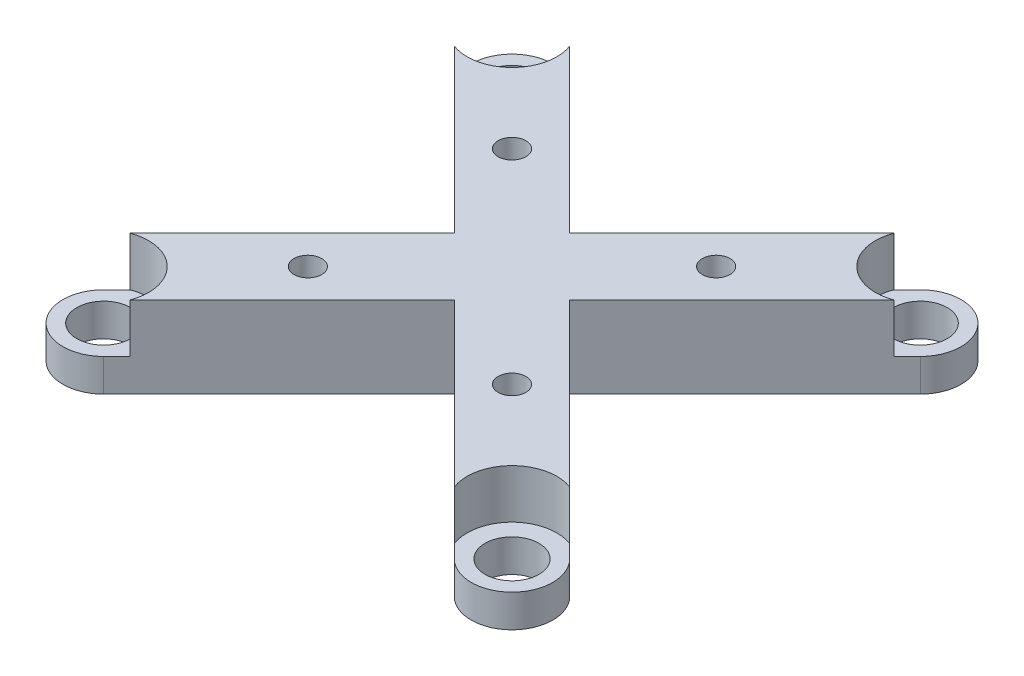
SolidWorks part; units mm, degrees
ref_plane "Front Plane" through (0, 0, 0) normal (0, 0, 1) x (1, 0, 0)
ref_plane "Top Plane" through (0, 0, 0) normal (0, 1, 0) x (1, 0, 0)
ref_plane "Right Plane" through (0, 0, 0) normal (1, 0, 0) x (0, 0, -1)
sketch "Sketch1" plane through (0, 0, 0) normal (0, 1, 0) x (1, 0, 0)
  line L0 (7.0711, 0) -> (28.5355, 21.4645)
  line L1 (0, 40.829) -> (0, -52.7147) construction
  line L2 (-50.9666, 0) -> (60.5221, 0) construction
  line L3 (0, 7.0711) -> (21.4645, 28.5355)
  line L4 (-7.0711, 0) -> (-28.5355, -21.4645)
  line L5 (0, 7.0711) -> (-21.4645, 28.5355)
  line L6 (-7.0711, 0) -> (-28.5355, 21.4645)
  line L7 (0, -7.0711) -> (-21.4645, -28.5355)
  line L8 (0, -7.0711) -> (21.4645, -28.5355)
  line L9 (7.0711, 0) -> (28.5355, -21.4645)
  arc A0 (-28.5355, 21.4645) -> (-21.4645, 28.5355) centre (-25, 25) cw
  arc A1 (28.5355, 21.4645) -> (21.4645, 28.5355) centre (25, 25) ccw
  arc A2 (28.5355, -21.4645) -> (21.4645, -28.5355) centre (25, -25) cw
  arc A3 (-28.5355, -21.4645) -> (-21.4645, -28.5355) centre (-25, -25) ccw
extrude "Extrude1" add sketch "Sketch1" along normal blind 10
hole_wizard "CBORE for M6 SHCS2" positions "3DSketch3" profile "Sketch4" counterbore size "M6" standard "Ansi Metric" end condition through all
sketch3d "3DSketch3"
  line L0 (-25, 10, -25) -> (-25, 0, -25) construction
  point P0 (-25, 10, -25)
sketch "Sketch4" plane through (-25, 10, -25) normal (1, 0, 0) x (0, 0, 1)
  line L0 (0, 0) -> (0, 10)
  line L1 (0, 10) -> (3.3, 10)
  line L3 (3.3, 10) -> (3.3, 6)
  line L4 (3.3, 6) -> (5.5, 6)
  line L5 (5.5, 6) -> (5.5, 0)
  line L7 (5.5, 0) -> (0, 0)
  line L11 (0, -6.35) -> (0, 107.95) construction
  dimension "Thru Hole Dia." = 6.6
  dimension "Thru Hole Depth" = 10
  dimension "C'Bore Dia." = 11
  dimension "C'Bore Depth" = 6
sketch "Sketch5" plane through (0, 10, 0) normal (0, 1, 0) x (-1, 0, 0)
  line L0 (2.714, -72.0956) -> (5.057, -74.4387) construction
  line L1 (48.8287, 0) -> (-52.8582, 0) construction
  line L2 (0, -47.4963) -> (0, 48.5979) construction
pattern_linear "LPattern1" count 2 spacing 50 along (1, 0, 0) count 2 spacing 50 along (0, 0, 1) of "CBORE for M6 SHCS2"
sketch "Sketch6" plane through (0, 0, 0) normal (0, -1, 0) x (1, 0, 0)
  line L0 (48.2279, 0) -> (-44.4046, 0) construction
  line L1 (0, -48.4741) -> (0, 45.1947) construction
hole_wizard "CBORE for M3 SHCS1" positions "3DSketch4" profile "Sketch7" counterbore size "M3" standard "Ansi Metric" end condition through all
sketch3d "3DSketch4"
  line L0 (48.2279, 0, 0) -> (-44.4046, 0, 0) construction
  line L1 (0, 0, -48.4741) -> (0, 0, 45.1947) construction
  point P0 (-12.5, 0, 12.5)
  dimension "D1" = 12.5
  dimension "D2" = 12.5
sketch "Sketch7" plane through (-12.5, 0, 12.5) normal (1, 0, 0) x (0, 0, -1)
  line L0 (0, 0) -> (0, 10)
  line L1 (0, 10) -> (1.7, 10)
  line L3 (1.7, 10) -> (1.7, 3)
  line L4 (1.7, 3) -> (3.25, 3)
  line L5 (3.25, 3) -> (3.25, 0)
  line L7 (3.25, 0) -> (0, 0)
  line L11 (0, -6.35) -> (0, 107.95) construction
  dimension "Thru Hole Dia." = 3.4
  dimension "Thru Hole Depth" = 10
  dimension "C'Bore Dia." = 6.5
  dimension "C'Bore Depth" = 3
pattern_linear "LPattern2" count 2 spacing 25 along (1, 0, 0) count 2 spacing 25 along (0, 0, -1) of "CBORE for M3 SHCS1"
